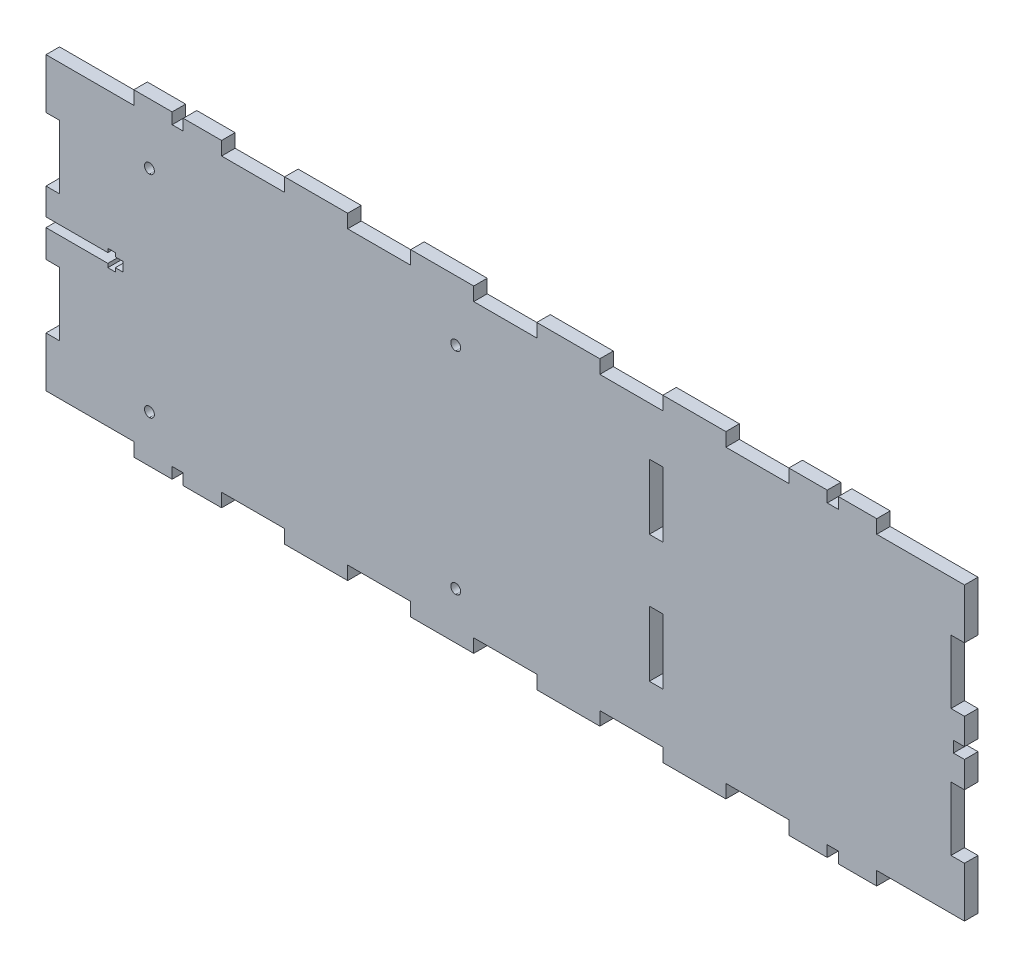
SolidWorks part; units mm, degrees
ref_plane "Front Plane" through (0, 0, 0) normal (0, 0, 1) x (1, 0, 0)
ref_plane "Top Plane" through (0, 0, 0) normal (0, 1, 0) x (1, 0, 0)
ref_plane "Right Plane" through (0, 0, 0) normal (1, 0, 0) x (0, 0, -1)
sketch "Model" plane through (0, 0, 0) normal (0, 0, 1) x (1, 0, 0)
  line L0 (760.0508, -825.0027) -> (747.2757, -825.0027)
  line L1 (747.2757, -825.0027) -> (747.2757, -829.5027)
  line L2 (747.2757, -829.5027) -> (722.5258, -829.5027)
  line L3 (978.3006, -825.0027) -> (965.5256, -825.0027)
  line L4 (965.5256, -825.0027) -> (965.5256, -829.5027)
  line L5 (965.5256, -829.5027) -> (944.5256, -829.5027)
  line L6 (944.5256, -829.5027) -> (944.5256, -825.0027)
  line L7 (944.5256, -825.0027) -> (923.5257, -825.0027)
  line L8 (923.5257, -825.0027) -> (923.5257, -829.5027)
  line L9 (923.5257, -829.5027) -> (902.5254, -829.5027)
  line L10 (902.5254, -829.5027) -> (902.5254, -825.0027)
  line L11 (902.5254, -825.0027) -> (881.5255, -825.0027)
  line L12 (881.5255, -825.0027) -> (881.5255, -829.5027)
  line L13 (881.5255, -829.5027) -> (860.5256, -829.5027)
  line L14 (860.5256, -829.5027) -> (860.5256, -825.0027)
  line L15 (860.5256, -825.0027) -> (839.5257, -825.0027)
  line L16 (839.5257, -825.0027) -> (839.5257, -829.5027)
  line L17 (839.5257, -829.5027) -> (818.5258, -829.5027)
  line L18 (818.5258, -829.5027) -> (818.5258, -825.0027)
  line L19 (818.5258, -825.0027) -> (797.5255, -825.0027)
  line L20 (797.5255, -825.0027) -> (797.5255, -829.5027)
  line L21 (797.5255, -829.5027) -> (776.5256, -829.5027)
  line L22 (776.5256, -829.5027) -> (776.5256, -825.0027)
  line L23 (776.5256, -825.0027) -> (763.7508, -825.0027)
  line L24 (1019.5257, -829.5027) -> (994.7754, -829.5027)
  line L25 (994.7754, -829.5027) -> (994.7754, -825.0027)
  line L26 (994.7754, -825.0027) -> (982.0007, -825.0027)
  line L27 (1024.0257, -829.5027) -> (1024.0257, -846.2028)
  line L28 (1024.0257, -846.2028) -> (1019.5257, -846.2028)
  line L29 (1019.5257, -846.2028) -> (1019.5257, -867.4025)
  line L30 (1019.5257, -867.4025) -> (1024.0257, -867.4025)
  line L31 (1024.0257, -867.4025) -> (1024.0257, -876.1527)
  line L32 (1024.0257, -876.1527) -> (1020.3257, -876.1527)
  line L33 (1020.3257, -876.1527) -> (1020.3257, -879.8522)
  line L34 (1020.3257, -879.8522) -> (1024.0257, -879.8522)
  line L35 (1024.0257, -879.8522) -> (1024.0257, -888.6028)
  line L36 (1024.0257, -888.6028) -> (1019.5257, -888.6028)
  line L37 (1019.5257, -888.6028) -> (1019.5257, -909.8025)
  line L38 (1019.5257, -909.8025) -> (1024.0257, -909.8025)
  line L39 (1024.0257, -909.8025) -> (1024.0257, -926.5023)
  line L40 (1024.0257, -926.5023) -> (994.7758, -926.5023)
  line L41 (994.7758, -926.5023) -> (994.7758, -931.0023)
  line L42 (994.7758, -931.0023) -> (982.0007, -931.0023)
  line L43 (982.0007, -931.0023) -> (982.0007, -927.3022)
  line L44 (982.0007, -927.3022) -> (978.3006, -927.3022)
  line L45 (978.3006, -927.3022) -> (978.3006, -931.0023)
  line L46 (978.3006, -931.0023) -> (965.5256, -931.0023)
  line L47 (965.5256, -931.0023) -> (965.5256, -926.5023)
  line L48 (965.5256, -926.5023) -> (944.5256, -926.5023)
  line L49 (944.5256, -926.5023) -> (944.5256, -931.0023)
  line L50 (944.5256, -931.0023) -> (923.5257, -931.0023)
  line L51 (923.5257, -931.0023) -> (923.5257, -926.5023)
  line L52 (923.5257, -926.5023) -> (902.5258, -926.5023)
  line L53 (902.5258, -926.5023) -> (902.5258, -931.0023)
  line L54 (902.5258, -931.0023) -> (881.5259, -931.0023)
  line L55 (881.5259, -931.0023) -> (881.5259, -926.5023)
  line L56 (881.5259, -926.5023) -> (860.5256, -926.5023)
  line L57 (860.5256, -926.5023) -> (860.5256, -931.0023)
  line L58 (860.5256, -931.0023) -> (839.5257, -931.0023)
  line L59 (839.5257, -931.0023) -> (839.5257, -926.5023)
  line L60 (839.5257, -926.5023) -> (818.5258, -926.5023)
  line L61 (818.5258, -926.5023) -> (818.5258, -931.0023)
  line L62 (818.5258, -931.0023) -> (797.5255, -931.0023)
  line L63 (797.5255, -931.0023) -> (797.5255, -926.5023)
  line L64 (797.5255, -926.5023) -> (776.5256, -926.5023)
  line L65 (776.5256, -926.5023) -> (776.5256, -931.0023)
  line L66 (776.5256, -931.0023) -> (763.7508, -931.0023)
  line L67 (763.7508, -931.0023) -> (763.7508, -927.3022)
  line L68 (763.7508, -927.3022) -> (760.0508, -927.3022)
  line L69 (760.0508, -927.3022) -> (760.0508, -931.0023)
  line L70 (760.0508, -931.0023) -> (747.2757, -931.0023)
  line L71 (747.2757, -931.0023) -> (747.2757, -926.5023)
  line L72 (747.2757, -926.5023) -> (718.0258, -926.5023)
  line L73 (718.0258, -926.5023) -> (718.0258, -909.8025)
  line L74 (718.0258, -909.8025) -> (722.5258, -909.8025)
  line L75 (722.5258, -909.8025) -> (722.5258, -888.6028)
  line L76 (722.5258, -888.6028) -> (718.0258, -888.6028)
  line L77 (718.0258, -888.6028) -> (718.0258, -879.4109)
  line L78 (978.3006, -825.0027) -> (978.3006, -828.7027)
  line L79 (978.3006, -828.7027) -> (982.0007, -828.7027)
  line L80 (982.0007, -828.7027) -> (982.0007, -825.0027)
  line L81 (760.0508, -825.0027) -> (760.0508, -828.7027)
  line L82 (760.0508, -828.7027) -> (763.7508, -828.7027)
  line L83 (763.7508, -828.7027) -> (763.7508, -825.0027)
  line L84 (718.0258, -876.311) -> (718.0258, -867.4025)
  line L85 (718.0258, -867.4025) -> (722.5258, -867.4025)
  line L86 (722.5258, -867.4025) -> (722.5258, -846.2028)
  line L87 (722.5258, -846.2028) -> (718.0258, -846.2028)
  line L88 (718.0258, -846.2028) -> (718.0258, -829.5027)
  line L89 (718.0258, -879.4109) -> (738.6259, -879.4109)
  line L90 (738.6259, -879.4109) -> (738.6259, -880.6608)
  line L91 (738.6259, -880.6608) -> (741.126, -880.6608)
  line L92 (741.126, -880.6608) -> (741.126, -879.4109)
  line L93 (741.126, -879.4109) -> (743.6259, -879.4109)
  line L94 (743.6259, -879.4109) -> (743.6259, -876.311)
  line L95 (743.6259, -876.311) -> (741.126, -876.311)
  line L96 (741.126, -876.311) -> (741.126, -875.0612)
  line L97 (741.126, -875.0612) -> (738.6259, -875.0612)
  line L98 (738.6259, -875.0612) -> (738.6259, -876.311)
  line L99 (738.6259, -876.311) -> (718.0258, -876.311)
  line L108 (923.5257, -867.4023) -> (919.0257, -867.4023)
  line L109 (919.0257, -867.4023) -> (919.0257, -845.7084)
  line L110 (919.0257, -845.7084) -> (923.5257, -845.7084)
  line L111 (923.5257, -845.7084) -> (923.5257, -867.4023)
  line L112 (919.0257, -909.8025) -> (923.5257, -909.8025)
  line L113 (923.5257, -909.8025) -> (923.5257, -888.1087)
  line L114 (923.5257, -888.1087) -> (919.0257, -888.1087)
  line L115 (919.0257, -888.1087) -> (919.0257, -909.8025)
  line L116 (718.0258, -829.5027) -> (722.5258, -829.5027)
  line L117 (1019.5257, -829.5027) -> (1024.0257, -829.5027)
  spline S0 degree 3 poles (752.476, -917.0028) (751.5648, -917.0028) (750.8262, -916.2641) (750.8262, -915.3526) (750.8262, -914.4417) (751.5648, -913.7024) (752.476, -913.7024) knots 2 2 2 2 3 3 3 4 4 4 4
  spline S1 degree 3 poles (752.476, -913.7024) (753.3872, -913.7024) (754.1262, -914.4417) (754.1262, -915.3526) (754.1262, -916.2641) (753.3872, -917.0028) (752.476, -917.0028) knots 0 0 0 0 1 1 1 2 2 2 2
  spline S2 degree 3 poles (752.476, -846.739) (751.5648, -846.739) (750.8262, -846.0004) (750.8262, -845.0888) (750.8262, -844.1779) (751.5648, -843.4386) (752.476, -843.4386) knots 2 2 2 2 3 3 3 4 4 4 4
  spline S3 degree 3 poles (752.476, -843.4386) (753.3872, -843.4386) (754.1262, -844.1779) (754.1262, -845.0888) (754.1262, -846.0004) (753.3872, -846.739) (752.476, -846.739) knots 0 0 0 0 1 1 1 2 2 2 2
  spline S4 degree 3 poles (854.5239, -917.0028) (853.6128, -917.0028) (852.8742, -916.2641) (852.8742, -915.3526) (852.8742, -914.4417) (853.6128, -913.7024) (854.5239, -913.7024) knots 2 2 2 2 3 3 3 4 4 4 4
  spline S5 degree 3 poles (854.5239, -913.7024) (855.4355, -913.7024) (856.1743, -914.4417) (856.1743, -915.3526) (856.1743, -916.2641) (855.4355, -917.0028) (854.5239, -917.0028) knots 0 0 0 0 1 1 1 2 2 2 2
  spline S6 degree 3 poles (854.5239, -846.7388) (853.6128, -846.7388) (852.8742, -846.0002) (852.8742, -845.0887) (852.8742, -844.1777) (853.6128, -843.4384) (854.5239, -843.4384) knots 2 2 2 2 3 3 3 4 4 4 4
  spline S7 degree 3 poles (854.5239, -843.4384) (855.4355, -843.4384) (856.1743, -844.1777) (856.1743, -845.0887) (856.1743, -846.0002) (855.4355, -846.7388) (854.5239, -846.7388) knots 0 0 0 0 1 1 1 2 2 2 2
extrude "Boss-Extrude1" add sketch "Model" along normal blind 4.5
